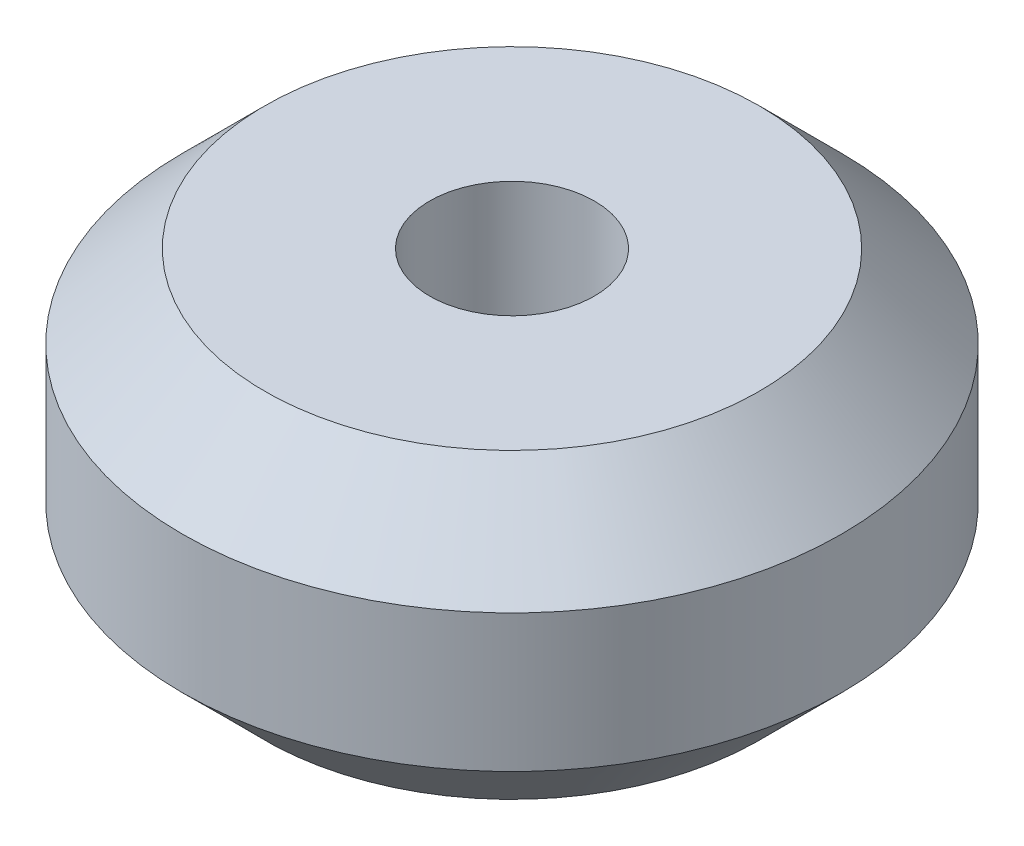
SolidWorks part; units mm, degrees
ref_plane "Спереди" through (0, 0, 0) normal (0, 0, 1) x (1, 0, 0)
ref_plane "Сверху" through (0, 0, 0) normal (0, 1, 0) x (1, 0, 0)
ref_plane "Справа" through (0, 0, 0) normal (1, 0, 0) x (0, 0, -1)
sketch "Эскиз1" plane through (0, 0, 0) normal (1, 0, 0) x (0, 0, -1)
  line L0 (9, 5.5) -> (12, 2.5)
  line L1 (3, 0) -> (12, 0)
  line L2 (0, 0) -> (0, 5.5)
  line L3 (3, 5.5) -> (9, 5.5)
  line L4 (12, 0) -> (12, 2.5)
  line L5 (9, 5.5) -> (12, 5.5) construction
  line L6 (12, 5.5) -> (12, 2.5) construction
  line L7 (3, 5.5) -> (3, 0)
  line L8 (3, 5.5) -> (0, 5.5) construction
  line L9 (0, 0) -> (3, 0) construction
  dimension "D1" = 5.5
  dimension "D2" = 12
  dimension "D3" = 3
  dimension "D4" = 3
  dimension "D5" = 3
revolve "Повернуть1" add sketch "Эскиз1" angle 360 about L2
mirror "Зеркальное отражение1" about plane through (0, 0, 0) normal (0, 1, 0) of "Повернуть1"
